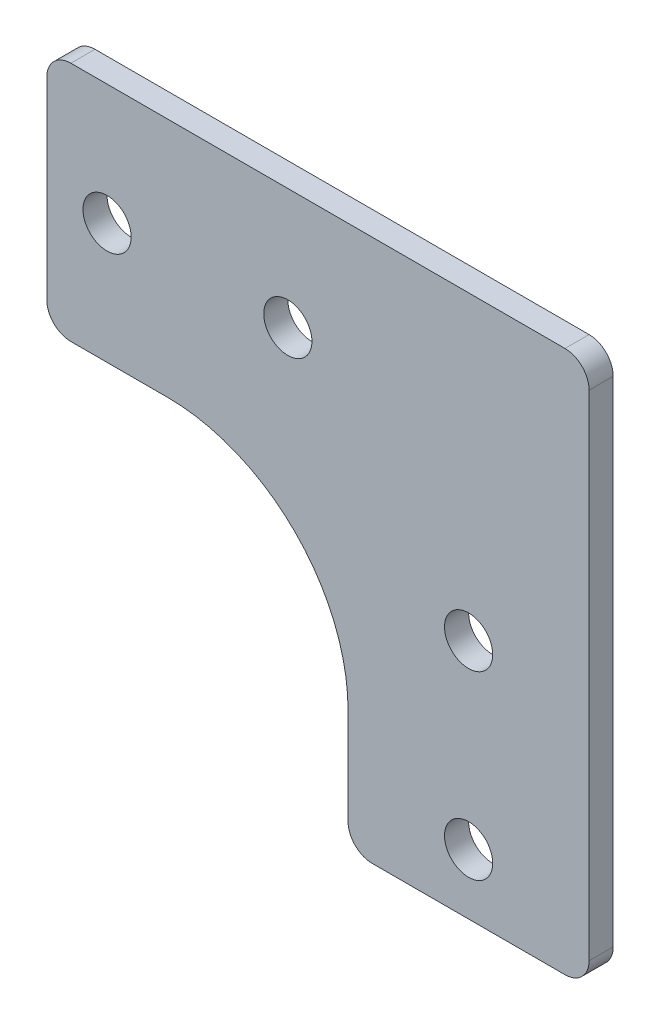
SolidWorks part; units mm, degrees
ref_plane "前视基准面" through (0, 0, 0) normal (0, 0, 1) x (1, 0, 0)
ref_plane "上视基准面" through (0, 0, 0) normal (0, 1, 0) x (1, 0, 0)
ref_plane "右视基准面" through (0, 0, 0) normal (1, 0, 0) x (0, 0, -1)
sketch "草图1" plane through (0, 0, 0) normal (0, 0, 1) x (1, 0, 0)
  line L0 (0, 0) -> (0, -45)
  line L1 (0, -45) -> (-20, -45)
  line L2 (-20, -45) -> (-20, -35)
  line L3 (-35, -20) -> (-45, -20)
  line L4 (-45, -20) -> (-45, 0)
  line L5 (-45, 0) -> (0, 0)
  arc A0 (-20, -35) -> (-35, -20) centre (-35, -35) ccw
  dimension "D5" = 15
  dimension "D1" = 20
  dimension "D2" = 20
  dimension "D3" = 45
  dimension "D4" = 45
extrude "凸台-拉伸1" add sketch "草图1" along normal blind 2
sketch "草图2" plane through (0, 0, 2) normal (0, 0, 1) x (1, 0, 0)
  line L0 (0, 0) -> (-45, 0) construction
  line L2 (0, -45) -> (0, 0) construction
  line L4 (0, 0) -> (-45, 0) construction
  circle A0 centre (-10, -40) radius 2
  circle A1 centre (-10, -25) radius 2
  circle A2 centre (-25, -10) radius 2
  circle A3 centre (-40, -10) radius 2
  point P10 (-7.5, -35.0764)
  point P11 (-19.1213, -7.5)
  dimension "D1" = 4
  dimension "D2" = 25
  dimension "D5" = 15
  dimension "D6" = 25
  dimension "D3" = 15
  dimension "D4" = 10
  dimension "D7" = 10
extrude "切除-拉伸1" cut sketch "草图2" against normal blind 2
fillet "圆角1" radius 2 5 edges at (0, -45, 1) (0, 0, 1) (-20, -45, 1) (-45, -20, 1) (-45, 0, 1)
